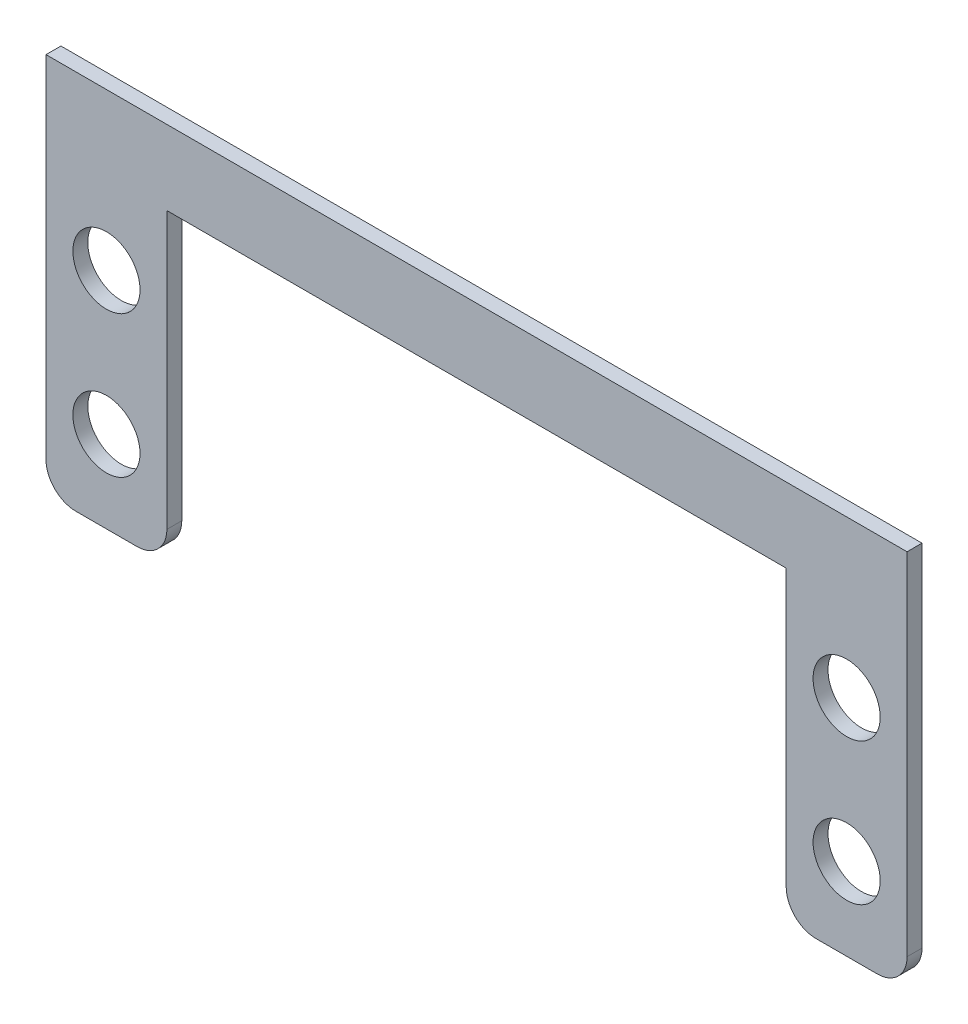
SolidWorks part; units mm, degrees
ref_plane "Front Plane" through (0, 0, 0) normal (0, 0, 1) x (1, 0, 0)
ref_plane "Top Plane" through (0, 0, 0) normal (0, 1, 0) x (1, 0, 0)
ref_plane "Right Plane" through (0, 0, 0) normal (1, 0, 0) x (0, 0, -1)
sketch "Sketch1" plane through (0, 0, 0) normal (0, 0, 1) x (1, 0, 0)
  line L0 (-43.5, -20.5) -> (-47.6, -20.5)
  line L1 (0, 0) -> (-41.5, 0)
  line L2 (0, 0) -> (0, -18.5)
  line L3 (-49.6, -18.5) -> (-49.6, 5)
  line L4 (-41.5, 0) -> (-41.5, -18.5)
  line L5 (-49.6, 5) -> (8.1, 5)
  line L6 (8.1, 5) -> (8.1, -18.5)
  line L7 (6.1, -20.5) -> (2, -20.5)
  circle A0 centre (-45.55, -5.5) radius 2.25
  circle A1 centre (-45.55, -15) radius 2.25
  circle A2 centre (4.05, -5.5) radius 2.25
  circle A3 centre (4.05, -15) radius 2.25
  arc A12 (-41.5, -18.5) -> (-43.5, -20.5) centre (-43.5, -18.5) cw
  arc A13 (-47.6, -20.5) -> (-49.6, -18.5) centre (-47.6, -18.5) cw
  arc A14 (0, -18.5) -> (2, -20.5) centre (2, -18.5) ccw
  arc A15 (8.1, -18.5) -> (6.1, -20.5) centre (6.1, -18.5) cw
  point P24 (-49.6, 5)
  point P26 (8.1, 5)
  point P51 (-41.5, -20.5)
  dimension "D8" = 4.5
  dimension "D9" = 4.5
  dimension "D10" = 4.5
  dimension "D11" = 4.5
  dimension "D19" = 4.05
  dimension "D20" = 25.5
  dimension "D23" = 2
  dimension "D1" = 41.5
  dimension "D2" = 20.5
  dimension "D3" = 0
  dimension "D4" = 57.7
  dimension "D5" = 4.05
  dimension "D6" = 4.05
  dimension "D7" = 20.5
  dimension "D12" = 9.5
  dimension "D13" = 9.5
  dimension "D14" = 5.5
  dimension "D15" = 5.5
  dimension "D16" = 57.7
  dimension "D17" = 8.1
  dimension "D18" = 4.05
extrude "Boss-Extrude1" add sketch "Sketch1" along normal blind 1
